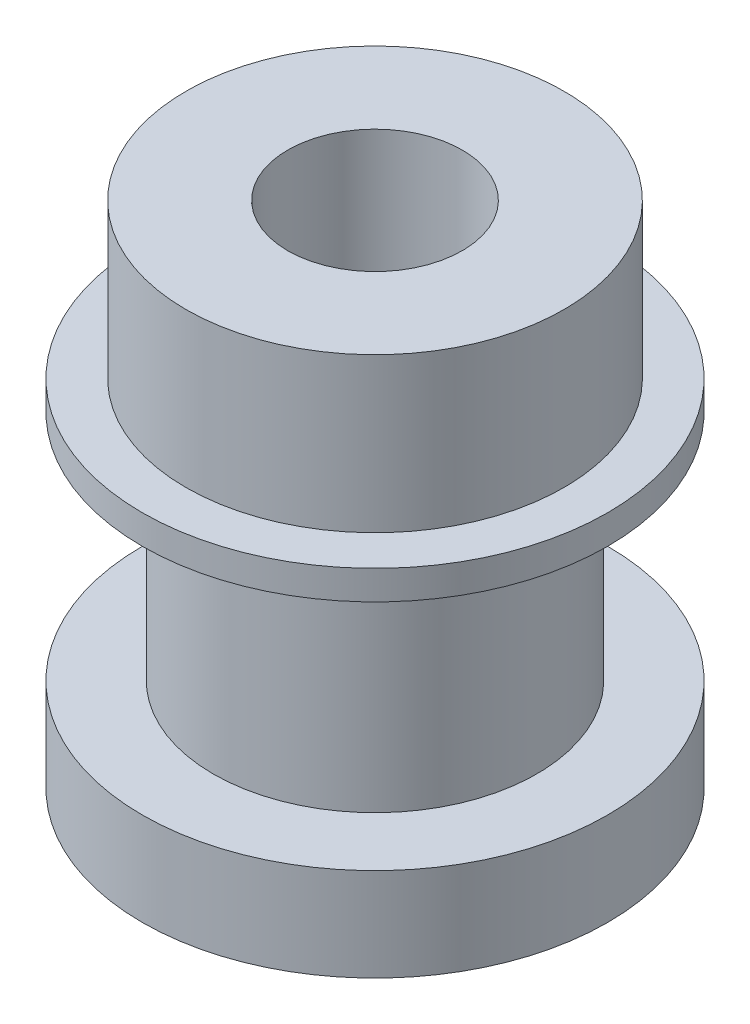
SolidWorks part; units mm, degrees
ref_plane "Front Plane" through (0, 0, 0) normal (0, 0, 1) x (1, 0, 0)
ref_plane "Top Plane" through (0, 0, 0) normal (0, 1, 0) x (1, 0, 0)
ref_plane "Right Plane" through (0, 0, 0) normal (1, 0, 0) x (0, 0, -1)
sketch "Sketch1" plane through (0, 0, 0) normal (0, 1, 0) x (1, 0, 0)
  circle A0 centre (0, 0) radius 6.5
extrude "Boss-Extrude1" add sketch "Sketch1" along normal blind 17.5
ref_plane "Plane1" through (0, 11.2, 0) normal (0, 1, 0) x (1, 0, 0)
sketch "Sketch2" plane through (0, 11.2, 0) normal (0, 1, 0) x (1, 0, 0)
  circle A0 centre (0, 0) radius 5.56
  circle A1 centre (0, 0) radius 8.6225
extrude "Cut-Extrude1" cut sketch "Sketch2" against normal blind 8
sketch "Sketch4" plane through (0, 17.5, 0) normal (0, 1, 0) x (1, 0, 0)
  circle A0 centre (0, 0) radius 3
extrude "Cut-Extrude2" cut sketch "Sketch4" against normal through all and the other way through all
sketch "Sketch5" plane through (0, 11.2, 0) normal (0, 1, 0) x (1, 0, 0)
  circle A0 centre (0, 0) radius 3.8692
  circle A1 centre (0, 0) radius 8
extrude "Boss-Extrude2" add sketch "Sketch5" along normal blind 1
sketch "Sketch6" plane through (0, 0, 0) normal (0, 1, 0) x (1, 0, 0)
  circle A0 centre (0, 0) radius 8
  circle A1 centre (0, 0) radius 3
extrude "Boss-Extrude3" add sketch "Sketch6" along normal blind 3.2
